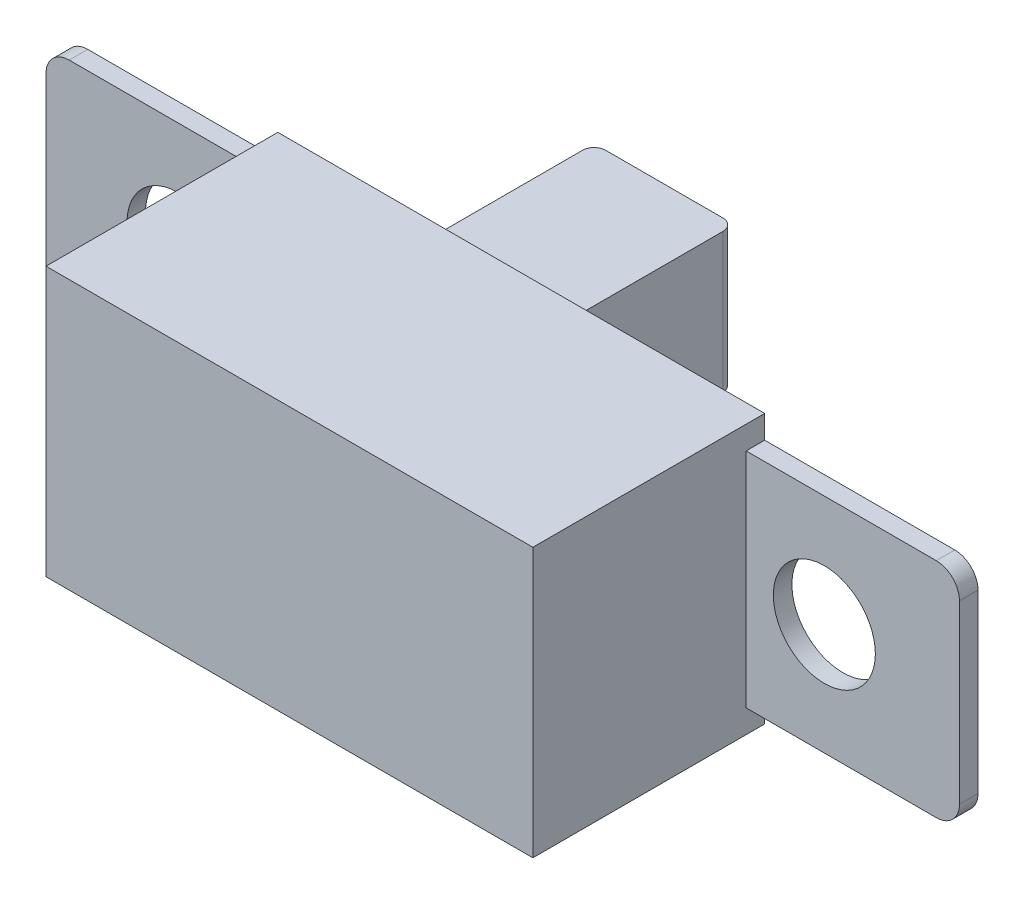
SolidWorks part; units mm, degrees
material "1023 Tôle d'acier au carbone (SS)"
ref_plane "Plan de face" through (0, 0, 0) normal (0, 0, 1) x (1, 0, 0)
ref_plane "Plan de dessus" through (0, 0, 0) normal (0, 1, 0) x (1, 0, 0)
ref_plane "Plan de droite" through (0, 0, 0) normal (1, 0, 0) x (0, 0, -1)
sketch "Esquisse1" plane through (0, 0, 0) normal (0, 0, 1) x (1, 0, 0)
  line L0 (0, 0) -> (-7.002, 0) construction
  line L1 (-5.25, -2.9) -> (5.25, -2.9)
  line L2 (-5.25, -2.9) -> (-5.25, -2.4)
  line L3 (-5.25, 2.9) -> (5.25, 2.9)
  line L4 (5.25, -2.9) -> (5.25, -2.4)
  line L5 (-5.25, -2.9) -> (5.25, 2.9) construction
  line L6 (-5.25, 2.9) -> (5.25, -2.9) construction
  line L7 (-9.35, -2.4) -> (-5.25, -2.4)
  line L8 (-9.85, -1.9) -> (-9.85, 1.9)
  line L9 (-9.35, 2.4) -> (-5.25, 2.4)
  line L10 (9.85, -1.9) -> (9.85, 1.9)
  line L11 (-9.85, -2.4) -> (9.85, 2.4) construction
  line L12 (-9.85, 2.4) -> (9.85, -2.4) construction
  line L13 (-0.0619, 0) -> (6.9363, 0) construction
  line L14 (5.25, 2.4) -> (9.35, 2.4)
  line L15 (-5.25, 2.4) -> (-5.25, 2.9)
  line L16 (5.25, -2.4) -> (9.35, -2.4)
  line L17 (5.25, 2.4) -> (5.25, 2.9)
  line L19 (-3.4841, -1.5) -> (3.3604, -1.5)
  line L20 (-3.4841, -1.5) -> (-3.4841, 1.5)
  line L21 (-3.4841, 1.5) -> (3.3604, 1.5)
  line L22 (3.3604, -1.5) -> (3.3604, 1.5)
  line L23 (-3.4841, -1.5) -> (3.3604, 1.5) construction
  line L24 (-3.4841, 1.5) -> (3.3604, -1.5) construction
  circle A0 centre (-7.002, 0) radius 1.1
  circle A1 centre (6.9363, 0) radius 1.1
  arc A2 (9.35, -2.4) -> (9.85, -1.9) centre (9.35, -1.9) ccw
  arc A3 (9.35, 2.4) -> (9.85, 1.9) centre (9.35, 1.9) cw
  arc A4 (-9.35, -2.4) -> (-9.85, -1.9) centre (-9.35, -1.9) cw
  arc A5 (-9.85, 1.9) -> (-9.35, 2.4) centre (-9.35, 1.9) cw
  point P0 (0, 0)
  point P6 (0, 0)
  dimension "D5" = 0.5
  dimension "D1" = 10.5
  dimension "D2" = 5.8
  dimension "D3" = 19.7
  dimension "D4" = 4.8
  dimension "D6" = 3
extrude "Boss.-Extru.1" add sketch "Esquisse1" along normal blind 0.4
sketch "Esquisse3" plane through (0, 2.9, 0) normal (0, 1, 0) x (1, 0, 0)
  line L2 (-5.25, -0.4) -> (5.25, -0.4)
  line L3 (-5.25, -0.4) -> (-5.25, -5)
  line L4 (-5.25, -5) -> (5.25, -5)
  line L5 (5.25, -0.4) -> (5.25, -5)
  dimension "D1" = 4.6
extrude "Boss.-Extru.3" add sketch "Esquisse3" against normal up to surface (5.8 mm away) up to face at (0, -2.9, 0.2)
sketch "Esquisse4" plane through (0, 0, 0.4) normal (0, 0, -1) x (-1, 0, 0)
  line L0 (3.4841, -1.5) -> (-3.3604, -1.5) construction
  line L1 (-3.3604, 1.5) -> (3.4841, 1.5) construction
  line L2 (3.0291, -1.5) -> (0, -1.5)
  line L3 (3.0291, -1.5) -> (3.0291, 1.5)
  line L4 (3.0291, 1.5) -> (0, 1.5)
  line L5 (0, -1.5) -> (0, 1.5)
extrude "Boss.-Extru.4" add sketch "Esquisse4" along normal blind 5
fillet "Congé1" radius 0.25 2 edges at (-3.0291, 0, -4.6) (0, 0, -4.6)
